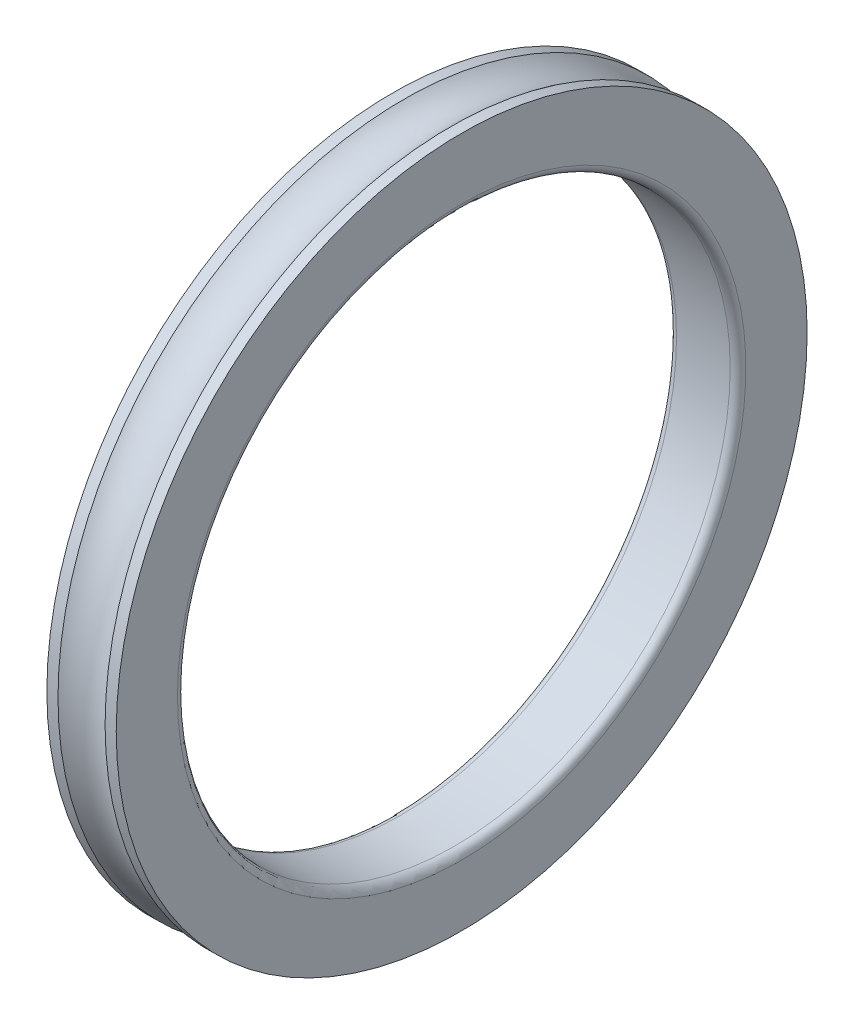
SolidWorks part; units mm, degrees
ref_plane "Front Plane" through (0, 0, 0) normal (0, 0, 1) x (1, 0, 0)
ref_plane "Top Plane" through (0, 0, 0) normal (0, 1, 0) x (1, 0, 0)
ref_plane "Right Plane" through (0, 0, 0) normal (1, 0, 0) x (0, 0, -1)
sketch "Sketch1" plane through (0, 0, 0) normal (0, 0, 1) x (1, 0, 0)
  line L0 (-23.1951, 0) -> (35.9677, 0) construction
  line L1 (0, 22.352) -> (0, 0) construction
  line L2 (2.8051, 27.94) -> (1.905, 27.94)
  line L3 (2.8051, 27.94) -> (2.8051, 22.987)
  line L4 (2.1701, 22.352) -> (-2.1701, 22.352)
  line L5 (-2.8051, 27.94) -> (-2.8051, 22.987)
  line L6 (2.8051, 27.94) -> (-2.8051, 22.352) construction
  line L7 (2.8051, 22.352) -> (-2.8051, 27.94) construction
  line L8 (-1.905, 27.94) -> (-2.8051, 27.94)
  arc A0 (-1.905, 27.94) -> (1.905, 27.94) centre (0, 30.48) ccw
  arc A1 (2.8051, 22.987) -> (2.1701, 22.352) centre (2.1701, 22.987) cw
  arc A2 (-2.1701, 22.352) -> (-2.8051, 22.987) centre (-2.1701, 22.987) cw
  point P3 (0, 25.146)
  dimension "D6" = 3.175
  dimension "D7" = 0.635
  dimension "D1" = 22.352
  dimension "D2" = 0.9001
  dimension "D3" = 5.588
  dimension "D4" = 0
  dimension "D5" = 2.54
revolve "Revolve1" add sketch "Sketch1" angle 360 about L0
